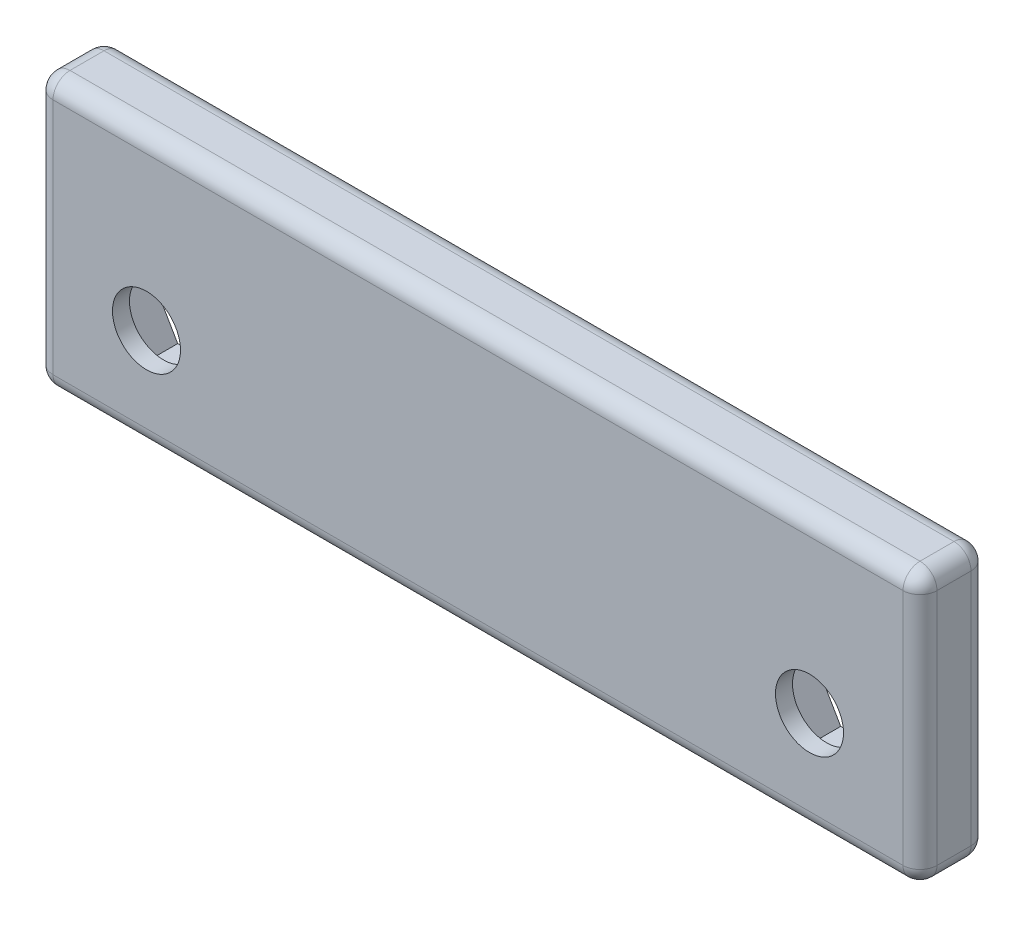
SolidWorks part; units mm, degrees
ref_plane "Front Plane" through (0, 0, 0) normal (0, 0, 1) x (1, 0, 0)
ref_plane "Top Plane" through (0, 0, 0) normal (0, 1, 0) x (1, 0, 0)
ref_plane "Right Plane" through (0, 0, 0) normal (1, 0, 0) x (0, 0, -1)
sketch "Sketch1" plane through (0, 0, 0) normal (0, 0, 1) x (1, 0, 0)
  line L1 (-12.1447, 9.7017) -> (39.8553, 9.7017)
  line L2 (-12.1447, 9.7017) -> (-12.1447, -6.2983)
  line L3 (-12.1447, -6.2983) -> (39.8553, -6.2983)
  line L4 (39.8553, 9.7017) -> (39.8553, -6.2983)
  circle A0 centre (-5.6447, -0.2983) radius 2
  circle A1 centre (33.3553, -0.2983) radius 2
  dimension "D3" = 4
  dimension "D4" = 4
  dimension "D1" = 16
  dimension "D2" = 52
  dimension "D5" = 39
  dimension "D6" = 6.5
  dimension "D7" = 10
  dimension "D8" = 10
extrude "Boss-Extrude1" add sketch "Sketch1" along normal blind 4
fillet "Fillet1" radius 1 12 edges at (-12.1447, 9.7017, 2) (-12.1447, 1.7017, 0) (-12.1447, 1.7017, 4) (-12.1447, -6.2983, 2) (13.8553, -6.2983, 0) (13.8553, -6.2983, 4) (39.8553, -6.2983, 2) (39.8553, 1.7017, 0) (39.8553, 1.7017, 4) (39.8553, 9.7017, 2) (13.8553, 9.7017, 0) (13.8553, 9.7017, 4)
sketch "Sketch5" plane through (0, 0, 0) normal (0, 0, -1) x (-1, 0, 0)
  line L1 (-29.0251, -0.2983) -> (-31.1902, 3.4517)
  line L2 (-31.1902, 3.4517) -> (-35.5203, 3.4517)
  line L3 (-35.5203, 3.4517) -> (-37.6854, -0.2983)
  line L4 (-37.6854, -0.2983) -> (-35.5203, -4.0483)
  line L5 (-35.5203, -4.0483) -> (-31.1902, -4.0483)
  line L6 (-31.1902, -4.0483) -> (-29.0251, -0.2983)
  line L7 (1.3146, -0.2983) -> (3.4797, -4.0483)
  line L8 (3.4797, -4.0483) -> (7.8098, -4.0483)
  line L9 (7.8098, -4.0483) -> (9.9749, -0.2983)
  line L10 (9.9749, -0.2983) -> (7.8098, 3.4517)
  line L11 (7.8098, 3.4517) -> (3.4797, 3.4517)
  line L12 (3.4797, 3.4517) -> (1.3146, -0.2983)
  circle A0 centre (-33.3553, -0.2983) radius 3.75 construction
  circle A1 centre (5.6447, -0.2983) radius 3.75 construction
  dimension "D1" = 7.5
  dimension "D2" = 7.5
extrude "Cut-Extrude1" cut sketch "Sketch5" against normal blind 3
